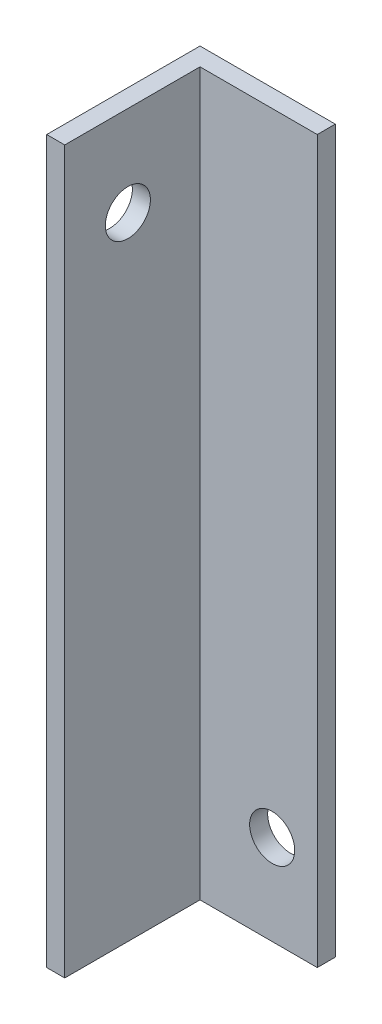
SolidWorks part; units mm, degrees
ref_plane "Plan de face" through (0, 0, 0) normal (0, 0, 1) x (1, 0, 0)
ref_plane "Plan de dessus" through (0, 0, 0) normal (0, 1, 0) x (1, 0, 0)
ref_plane "Plan de droite" through (0, 0, 0) normal (1, 0, 0) x (0, 0, -1)
sketch "Esquisse1" plane through (0, 0, 0) normal (0, 0, 1) x (1, 0, 0)
  line L1 (0, 0) -> (15, 0)
  line L2 (0, 0) -> (0, -80)
  line L3 (0, -80) -> (15, -80)
  line L4 (15, 0) -> (15, -80)
  dimension "D1" = 15
  dimension "D2" = 80
extrude "Boss.-Extru.1" add sketch "Esquisse1" along normal blind 2
sketch "Esquisse2" plane through (0, 0, 2) normal (0, 0, 1) x (1, 0, 0)
  line L0 (0, -80) -> (15, -80) construction
  line L1 (0, 0) -> (2, 0)
  line L2 (0, 0) -> (0, -80)
  line L3 (0, -80) -> (2, -80)
  line L4 (2, 0) -> (2, -80)
  dimension "D1" = 2
extrude "Boss.-Extru.2" add sketch "Esquisse2" along normal blind 15
sketch "Esquisse3" plane through (0, 0, 2) normal (0, 0, 1) x (1, 0, 0)
  line L0 (0, -80) -> (15, -80) construction
  line L2 (15, -80) -> (15, 0) construction
  circle A0 centre (10, -70) radius 2.5
  dimension "D1" = 5
  dimension "D2" = 10
extrude "Enlèv. mat.-Extru.1" cut sketch "Esquisse3" against normal blind 20
sketch "Esquisse4" plane through (0, 0, 0) normal (-1, 0, 0) x (0, 0, 1)
  line L0 (0, 0) -> (0, -80) construction
  line L2 (17, 0) -> (0, 0) construction
  circle A0 centre (10, -10) radius 2.5
  dimension "D1" = 5
  dimension "D2" = 10
  dimension "D3" = 10
extrude "Enlèv. mat.-Extru.2" cut sketch "Esquisse4" against normal blind 20
